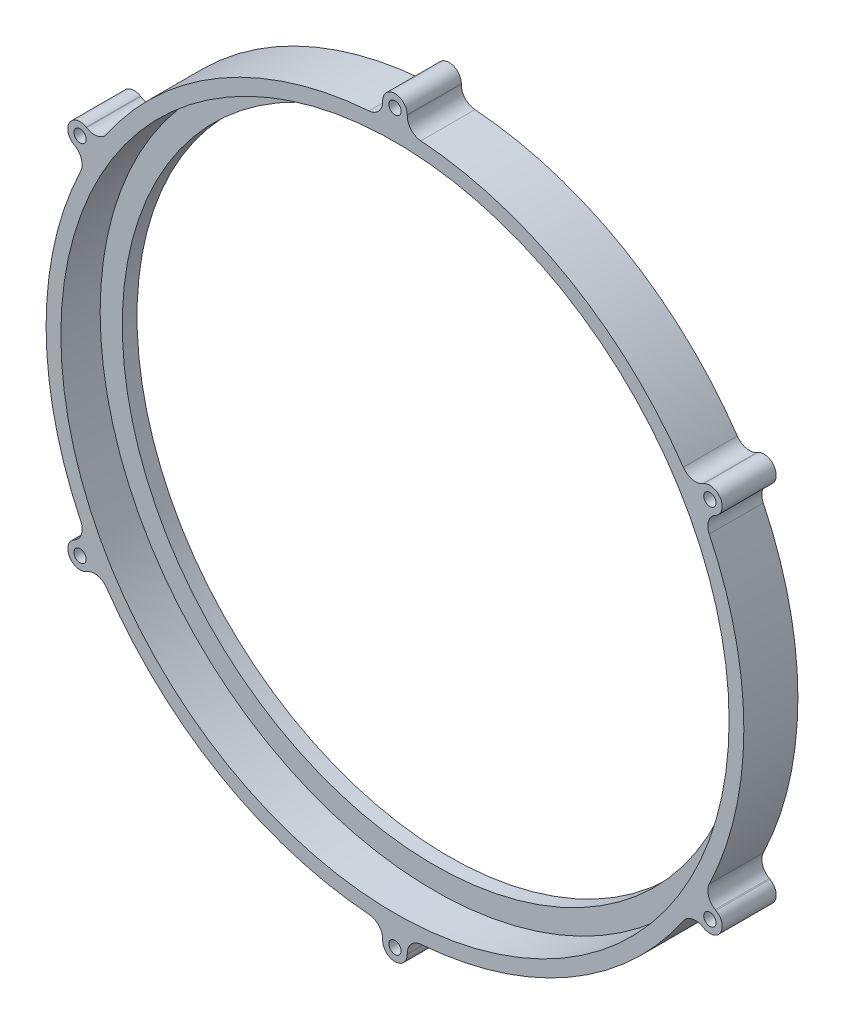
SolidWorks part; units mm, degrees
ref_plane "前视基准面" through (0, 0, 0) normal (0, 0, 1) x (1, 0, 0)
ref_plane "上视基准面" through (0, 0, 0) normal (0, 1, 0) x (1, 0, 0)
ref_plane "右视基准面" through (0, 0, 0) normal (1, 0, 0) x (0, 0, -1)
sketch "草图1" plane through (0, 0, 0) normal (0, 0, 1) x (1, 0, 0)
  circle A0 centre (0, 0) radius 63.5
  circle A1 centre (0, 0) radius 71
  dimension "D1" = 127
  dimension "D2" = 142
extrude "凸台-拉伸1" add sketch "草图1" along normal blind 3
sketch "草图2" plane through (0, 0, 3) normal (0, 0, 1) x (1, 0, 0)
  circle A0 centre (0, 0) radius 71
  circle A1 centre (0, 0) radius 68
  circle A2 centre (0, 0) radius 71 construction
  dimension "D1" = 3
extrude "凸台-拉伸2" add sketch "草图2" along normal blind 8
sketch "草图3" plane through (0, 0, 11) normal (0, 0, 1) x (1, 0, 0)
  line L0 (-2.5, 74) -> (-2.5, 70.956)
  line L1 (0, 74) -> (-64.0859, 37) construction
  line L2 (-64.0859, 37) -> (-64.0859, -37) construction
  line L3 (-64.0859, -37) -> (0, -74) construction
  line L4 (0, -74) -> (64.0859, -37) construction
  line L5 (64.0859, -37) -> (64.0859, 37) construction
  line L6 (64.0859, 37) -> (0, 74) construction
  line L7 (2.5, 74) -> (2.3973, 70.9595)
  line L8 (62.8359, 39.1651) -> (60.1997, 37.643)
  line L9 (65.3359, 34.8349) -> (62.6514, 33.4037)
  line L10 (65.3359, -34.8349) -> (62.6997, -33.3129)
  line L11 (62.8359, -39.1651) -> (60.2541, -37.5559)
  line L12 (2.5, -74) -> (2.5, -70.956)
  line L13 (-2.5, -74) -> (-2.3973, -70.9595)
  line L14 (-62.8359, -39.1651) -> (-60.1997, -37.643)
  line L15 (-65.3359, -34.8349) -> (-62.6514, -33.4037)
  line L16 (-65.3359, 34.8349) -> (-62.6997, 33.3129)
  line L17 (-62.8359, 39.1651) -> (-60.2541, 37.5559)
  circle A0 centre (0, 0) radius 74 construction
  circle A1 centre (0, 0) radius 64.0859 construction
  arc A2 (2.4943, 73.8313) -> (-2.4996, 73.9578) centre (0, 74) ccw
  arc A3 (2.3973, 70.9595) -> (-2.5, 70.956) centre (0, 0) ccw
  circle A4 centre (0, 0) radius 71 construction
  circle A5 centre (0, 74) radius 1.25
  arc A6 (-2.1651, 72.75) -> (2.1651, 72.75) centre (0, 74) ccw construction
  arc A7 (2.1651, 72.75) -> (2.4943, 73.8313) centre (0, 74) ccw construction
  arc A8 (-2.4996, 73.9578) -> (-2.1651, 72.75) centre (0, 74) ccw construction
  arc A9 (65.1869, 34.7555) -> (62.7995, 39.1436) centre (64.0859, 37) ccw
  circle A10 centre (64.0859, 37) radius 1.25
  arc A11 (62.6926, -39.0758) -> (65.2991, -34.8141) centre (64.0859, -37) ccw
  circle A12 centre (64.0859, -37) radius 1.25
  arc A13 (-2.4943, -73.8313) -> (2.4996, -73.9578) centre (0, -74) ccw
  circle A14 centre (0, -74) radius 1.25
  arc A15 (-65.1869, -34.7555) -> (-62.7995, -39.1436) centre (-64.0859, -37) ccw
  circle A16 centre (-64.0859, -37) radius 1.25
  arc A17 (-62.6926, 39.0758) -> (-65.2991, 34.8141) centre (-64.0859, 37) ccw
  circle A18 centre (-64.0859, 37) radius 1.25
  arc A19 (58.5099, 40.2193) -> (5.576, 70.7807) centre (0, 0) ccw construction
  arc A20 (62.6514, 33.4037) -> (60.1997, 37.643) centre (0, 0) ccw
  arc A21 (64.0859, -30.5614) -> (64.0859, 30.5614) centre (0, 0) ccw construction
  arc A22 (60.2541, -37.5559) -> (62.6997, -33.3129) centre (0, 0) ccw
  arc A23 (5.576, -70.7807) -> (58.5099, -40.2193) centre (0, 0) ccw construction
  arc A24 (58.5099, -40.2193) -> (60.2541, -37.5559) centre (0, 0) ccw construction
  arc A25 (62.6997, -33.3129) -> (64.0859, -30.5614) centre (0, 0) ccw construction
  arc A26 (60.1997, 37.643) -> (58.5099, 40.2193) centre (0, 0) ccw construction
  arc A27 (64.0859, 30.5614) -> (62.6514, 33.4037) centre (0, 0) ccw construction
  arc A28 (-60.2541, 37.5559) -> (-62.6997, 33.3129) centre (0, 0) ccw
  arc A29 (-5.576, 70.7807) -> (-58.5099, 40.2193) centre (0, 0) ccw construction
  arc A30 (5.576, 70.7807) -> (2.3973, 70.9595) centre (0, 0) ccw construction
  arc A31 (-2.5, 70.956) -> (-5.576, 70.7807) centre (0, 0) ccw construction
  arc A32 (-62.6514, -33.4037) -> (-60.1997, -37.643) centre (0, 0) ccw
  arc A33 (-64.0859, 30.5614) -> (-64.0859, -30.5614) centre (0, 0) ccw construction
  arc A34 (-62.6997, 33.3129) -> (-64.0859, 30.5614) centre (0, 0) ccw construction
  arc A35 (-58.5099, 40.2193) -> (-60.2541, 37.5559) centre (0, 0) ccw construction
  arc A36 (-2.3973, -70.9595) -> (2.5, -70.956) centre (0, 0) ccw
  arc A37 (-60.1997, -37.643) -> (-58.5099, -40.2193) centre (0, 0) ccw construction
  arc A38 (-58.5099, -40.2193) -> (-5.576, -70.7807) centre (0, 0) ccw construction
  arc A39 (-64.0859, -30.5614) -> (-62.6514, -33.4037) centre (0, 0) ccw construction
  arc A40 (2.5, -70.956) -> (5.576, -70.7807) centre (0, 0) ccw construction
  arc A41 (-5.576, -70.7807) -> (-2.3973, -70.9595) centre (0, 0) ccw construction
  point P65 (0, 0)
  dimension "D1" = 148
  dimension "D2" = 5
  dimension "D3" = 2.5
  dimension "D4" = 6
extrude "凸台-拉伸3" add sketch "草图3" against normal blind 11
cosmetic thread "装饰螺纹线1" parameters "D1"=5, "D2"=3
cosmetic thread "装饰螺纹线2" parameters "D1"=5, "D2"=3
cosmetic thread "装饰螺纹线3" parameters "D1"=5, "D2"=3
cosmetic thread "装饰螺纹线4" parameters "D1"=5, "D2"=3
cosmetic thread "装饰螺纹线5" parameters "D1"=5, "D2"=3
cosmetic thread "装饰螺纹线6" parameters "D1"=5, "D2"=3
fillet "圆角2" radius 3 12 edges at (-62.6514, -33.4037, 5.5) (-60.1997, -37.643, 5.5) (-2.3973, -70.9595, 5.5) (2.5, -70.956, 5.5) (60.2541, -37.5559, 5.5) (62.6997, -33.3129, 5.5) (62.6514, 33.4037, 5.5) (60.1997, 37.643, 5.5) (2.3973, 70.9595, 5.5) (-2.5, 70.956, 5.5) (-60.2541, 37.5559, 5.5) (-62.6997, 33.3129, 5.5)
